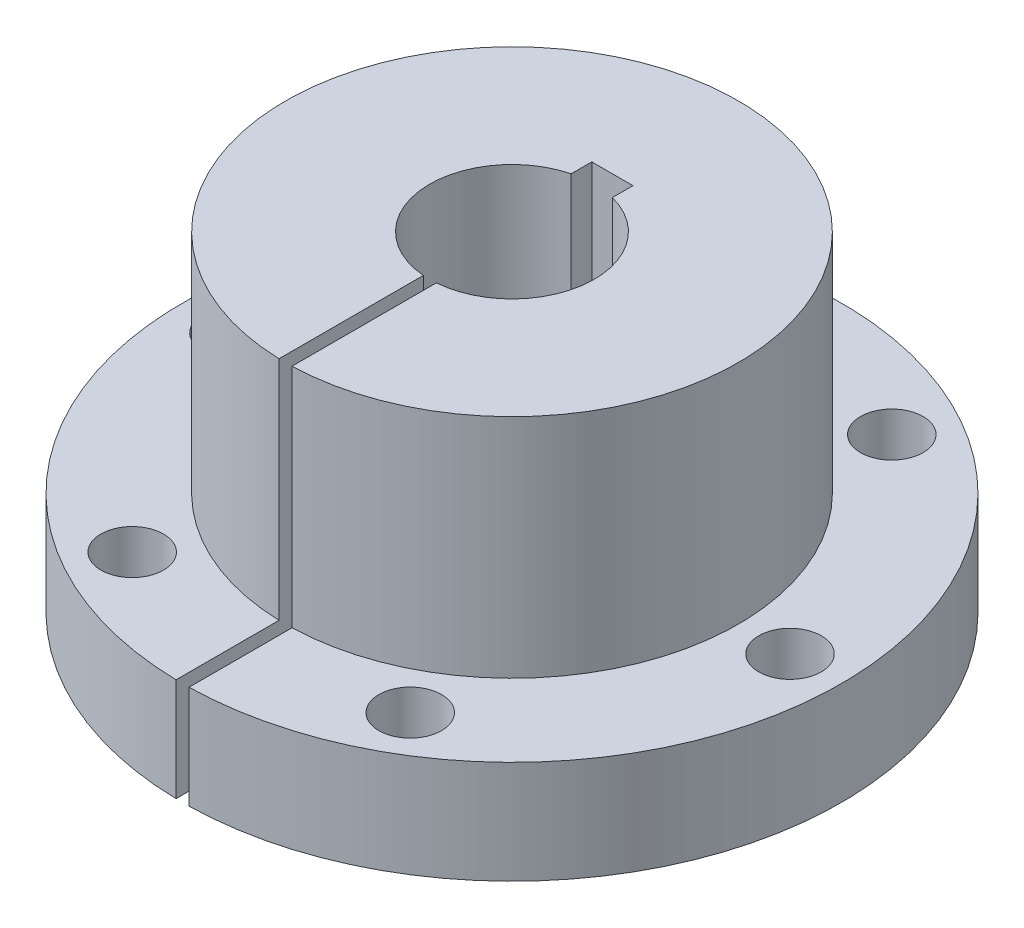
SolidWorks part; units mm, degrees
ref_plane "Front Plane" through (0, 0, 0) normal (0, 0, 1) x (1, 0, 0)
ref_plane "Top Plane" through (0, 0, 0) normal (0, 1, 0) x (1, 0, 0)
ref_plane "Right Plane" through (0, 0, 0) normal (1, 0, 0) x (0, 0, -1)
sketch "Sketch1" plane through (0, 0, 0) normal (0, 1, 0) x (1, 0, 0)
  circle A0 centre (0, 0) radius 25.4
  dimension "D1" = 50.8
extrude "Boss-Extrude1" add sketch "Sketch1" along normal blind 7.9375
sketch "Sketch2" plane through (0, 7.9375, 0) normal (0, 1, 0) x (1, 0, 0)
  circle A0 centre (0, 0) radius 17.4625
  dimension "D1" = 34.925
extrude "Boss-Extrude2" add sketch "Sketch2" along normal blind 17.4625
sketch "Sketch3" plane through (0, 25.4, 0) normal (0, 1, 0) x (1, 0, 0)
  line L0 (-1.5875, 7.7359) -> (1.5875, 7.7359)
  line L1 (-1.5875, 7.7359) -> (-1.5875, 6.1484)
  line L2 (1.5875, 7.7359) -> (1.5875, 6.1484)
  line L6 (-0.5, -6.3303) -> (-0.5, -25.4)
  line L7 (-0.5, -25.4) -> (0.5, -25.4)
  line L8 (0.5, -6.3303) -> (0.5, -25.4)
  arc A0 (-1.5875, 6.1484) -> (-0.5, -6.3303) centre (0, 0) ccw
  circle A1 centre (0, 0) radius 25.4 construction
  arc A2 (0.5, -6.3303) -> (1.5875, 6.1484) centre (0, 0) ccw
  point P10 (0, 0)
  point P12 (0, 0)
  point P13 (0, 0)
  point P16 (0, 0)
  dimension "D1" = 12.7
  dimension "D2" = 3.175
  dimension "D3" = 1.5875
  dimension "D4" = 1
extrude "Cut-Extrude1" cut sketch "Sketch3" against normal through all
sketch "Sketch4" plane through (0, 7.9375, 0) normal (0, 1, 0) x (1, 0, 0)
  line L0 (-23.8443, 0) -> (-25.4, 0) construction
  line L1 (-19.0182, 0) -> (-17.4625, 0) construction
  line L2 (0, 25.4) -> (-12.5308, 25.4) construction
  circle A0 centre (-21.4312, 0) radius 2.413
  arc A1 (0.5, -25.3951) -> (-0.5, -25.3951) centre (0, 0) ccw construction
  arc A2 (0.5, -17.4553) -> (-0.5, -17.4553) centre (0, 0) ccw construction
  dimension "D1" = 4.826
  dimension "D2" = 25.4
extrude "Cut-Extrude2" cut sketch "Sketch4" against normal through all
pattern_circular "CirPattern1" count 6 over 360 about axis through (0, 0, 0) along (0, 1, 0) of "Cut-Extrude2"
